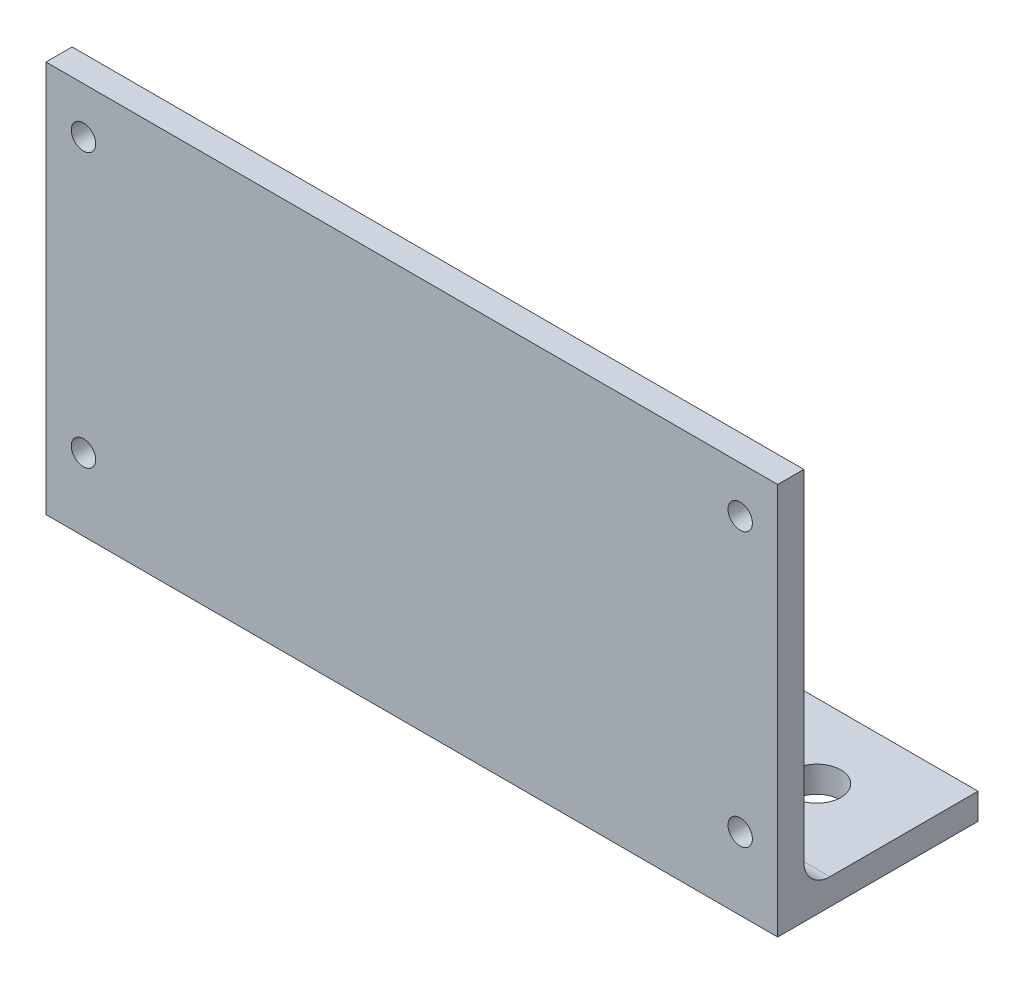
SolidWorks part; units mm, degrees
ref_plane "Front Plane" through (0, 0, 0) normal (0, 0, 1) x (1, 0, 0)
ref_plane "Top Plane" through (0, 0, 0) normal (0, 1, 0) x (1, 0, 0)
ref_plane "Right Plane" through (0, 0, 0) normal (1, 0, 0) x (0, 0, -1)
sketch "Sketch1" plane through (0, 0, 0) normal (0, 0, 1) x (1, 0, 0)
  line L1 (-42, -21) -> (42, -21)
  line L2 (-42, -21) -> (-42, 21)
  line L3 (-42, 21) -> (42, 21)
  line L4 (42, -21) -> (42, 21)
  line L5 (-42, -21) -> (42, 21) construction
  line L6 (-42, 21) -> (42, -21) construction
  line L7 (-37.7, -15.7) -> (37.7, -15.7) construction
  line L8 (-37.7, -15.7) -> (-37.7, 15.7) construction
  line L9 (-37.7, 15.7) -> (37.7, 15.7) construction
  line L10 (37.7, -15.7) -> (37.7, 15.7) construction
  line L11 (-37.7, -15.7) -> (37.7, 15.7) construction
  line L12 (-37.7, 15.7) -> (37.7, -15.7) construction
  circle A0 centre (-37.7, 15.7) radius 1.4
  circle A1 centre (37.7, 15.7) radius 1.4
  circle A2 centre (37.7, -15.7) radius 1.4
  circle A3 centre (-37.7, -15.7) radius 1.4
  point P0 (0, 0)
  point P6 (0, 0)
  dimension "D5" = 2.8
  dimension "D6" = 2.8
  dimension "D7" = 2.8
  dimension "D8" = 2.8
  dimension "D1" = 75.4
  dimension "D2" = 31.4
  dimension "D3" = 84
  dimension "D4" = 42
extrude "Boss-Extrude1" add sketch "Sketch1" along normal blind 3
sketch "Sketch2" plane through (0, 0, 0) normal (0, 0, -1) x (-1, 0, 0)
  line L1 (-42, -21) -> (42, -21)
  line L2 (-42, -21) -> (-42, -24)
  line L3 (-42, -24) -> (42, -24)
  line L4 (42, -21) -> (42, -24)
  dimension "D1" = 3
extrude "Boss-Extrude2" add sketch "Sketch2" along normal blind 20 and the other way up to surface (3 mm away) other way up to face at (0, 0, 3)
fillet "Fillet1" radius 3 1 edges at (0, -21, 0)
sketch "Sketch5" plane through (0, -21, 0) normal (0, 1, 0) x (1, 0, 0)
  line L0 (-42, 11.5) -> (42, 11.5) construction
  line L1 (-42, 3) -> (-42, 20) construction
  line L2 (42, 3) -> (42, 20) construction
  circle A0 centre (-32, 11.5) radius 2.75
  circle A1 centre (32, 11.5) radius 2.75
  dimension "D3" = 5.5
  dimension "D4" = 5.5
  dimension "D1" = 10
  dimension "D2" = 10
extrude "Cut-Extrude1" cut sketch "Sketch5" against normal up to surface (3 mm away) up to face at (0, -24, -8.5)
